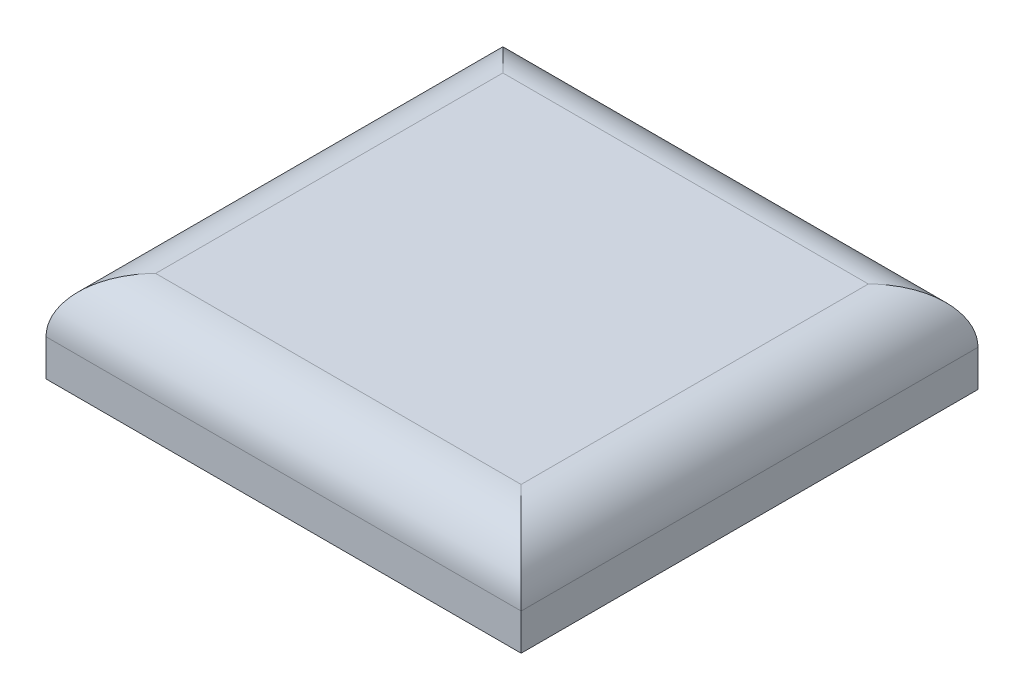
SolidWorks part; units mm, degrees
ref_plane "Front Plane" through (0, 0, 0) normal (0, 0, 1) x (1, 0, 0)
ref_plane "Top Plane" through (0, 0, 0) normal (0, 1, 0) x (1, 0, 0)
ref_plane "Right Plane" through (0, 0, 0) normal (1, 0, 0) x (0, 0, -1)
ref_plane "Plane1" through (0, 17.2, 0) normal (0, 1, 0) x (1, 0, 0)
sketch "Sketch2" plane through (0, 17.2, 0) normal (0, 1, 0) x (1, 0, 0)
  line L8 (-533.1261, -587.6566) -> (766.8739, -587.6566)
  line L9 (766.8739, -587.6566) -> (766.8739, 662.3434)
  line L10 (766.8739, 662.3434) -> (-533.1261, 662.3434)
  line L11 (-533.1261, 662.3434) -> (-533.1261, -587.6566)
  line L20 (-513.1261, -567.6566) -> (746.8739, -567.6566)
  line L21 (746.8739, -567.6566) -> (746.8739, 642.3434)
  line L22 (-513.1261, 642.3434) -> (-513.1261, -567.6566)
  line L23 (-513.1261, 642.3434) -> (746.8739, 642.3434)
extrude "Boss-Extrude1" add sketch "Sketch2" along normal blind 250 contours L11 L8 L9 L10
fillet "Fillet2" radius 150 4 edges at (766.8739, 267.2, -37.3434) (116.8739, 267.2, 587.6566) (-533.1261, 267.2, -37.3434) (116.8739, 267.2, -662.3434)
shell "Shell3" thickness 10
